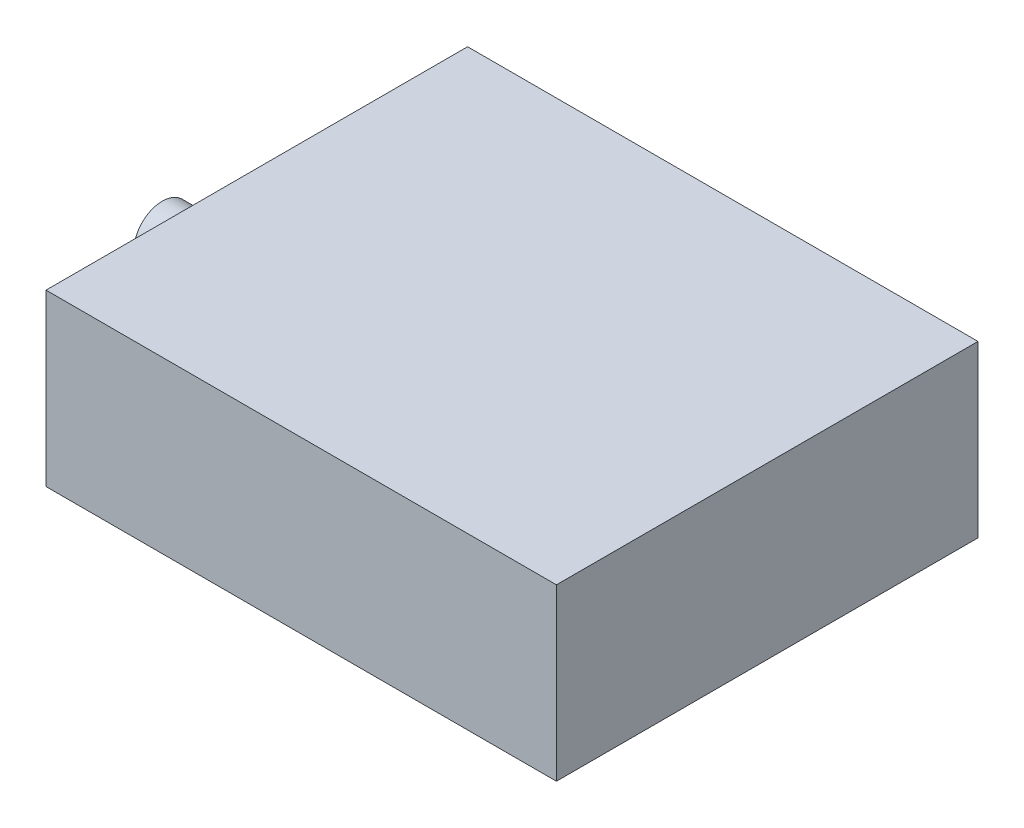
SolidWorks part; units mm, degrees
ref_plane "Front Plane" through (0, 0, 0) normal (0, 0, 1) x (1, 0, 0)
ref_plane "Top Plane" through (0, 0, 0) normal (0, 1, 0) x (1, 0, 0)
ref_plane "Right Plane" through (0, 0, 0) normal (1, 0, 0) x (0, 0, -1)
sketch "Sketch1" plane through (0, 0, 0) normal (0, 1, 0) x (1, 0, 0)
  line L1 (-13.5, -11.15) -> (13.5, -11.15)
  line L2 (-13.5, -11.15) -> (-13.5, 11.15)
  line L3 (-13.5, 11.15) -> (13.5, 11.15)
  line L4 (13.5, -11.15) -> (13.5, 11.15)
  line L5 (0, 11.15) -> (0, -11.15) construction
  line L6 (-13.5, 0) -> (13.5, 0) construction
  point P0 (0, 0)
  dimension "D1" = 27
  dimension "D2" = 22.3
extrude "Boss-Extrude1" add sketch "Sketch1" along normal blind 9
sketch "Sketch2" plane through (-13.5, 0, 0) normal (-1, 0, 0) x (0, 0, 1)
  line L0 (0, 9) -> (0, 0) construction
  line L1 (-11.15, 9) -> (11.15, 9) construction
  circle A0 centre (0, 3.5) radius 1.5
  point P7 (0, 2)
  dimension "D1" = 3
  dimension "D2" = 2
extrude "Boss-Extrude3" add sketch "Sketch2" along normal blind 5
